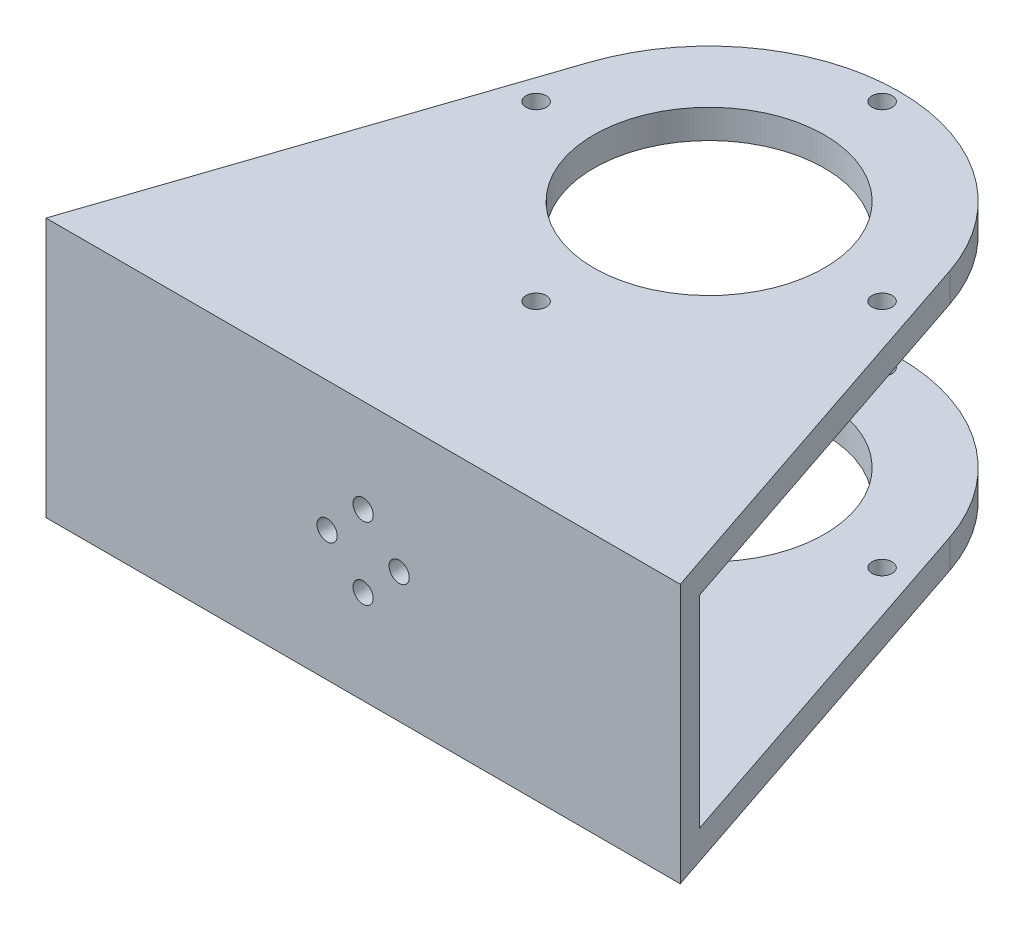
SolidWorks part; units mm, degrees
ref_plane "Front Plane" through (0, 0, 0) normal (0, 0, 1) x (1, 0, 0)
ref_plane "Top Plane" through (0, 0, 0) normal (0, 1, 0) x (1, 0, 0)
ref_plane "Right Plane" through (0, 0, 0) normal (1, 0, 0) x (0, 0, -1)
sketch "Sketch1" plane through (0, 0, 0) normal (0, 1, 0) x (1, 0, 0)
  line L0 (0, 0) -> (0, 56.3962) construction
  line L1 (-39.7228, 13.3621) -> (-69.85, -76.2)
  line L2 (-69.85, -76.2) -> (69.85, -76.2)
  line L3 (39.7228, 13.3621) -> (69.85, -76.2)
  arc A0 (39.7228, 13.3621) -> (-39.7228, 13.3621) centre (0, 0) ccw
  point P9 (0, -76.2)
  dimension "D1" = 139.7
  dimension "D2" = 41.91
  dimension "D3" = 76.2
extrude "Boss-Extrude1" add sketch "Sketch1" along normal blind 57.15 contours L1 L2 L3 A0
sketch "Sketch2" plane through (0, 57.15, 0) normal (0, 1, 0) x (1, 0, 0)
  circle A0 centre (0, 0) radius 25.4
  dimension "D1" = 50.8
extrude "Cut-Extrude1" cut sketch "Sketch2" against normal up to surface (57.15 mm away) up to face at (0, 0, 24.282)
sketch "Sketch3" plane through (0, 57.15, 0) normal (0, 1, 0) x (1, 0, 0)
  circle A0 centre (0, 0) radius 38.1 construction
  circle A1 centre (0, 38.1) radius 2.2225
  dimension "D1" = 76.2
  dimension "D2" = 4.445
extrude "Cut-Extrude2" cut sketch "Sketch3" against normal up to surface (57.15 mm away) contours A1 up to face at (0, 0, 25.4)
pattern_circular "CirPattern1" count 4 over 360 about axis through (0, 0, 0) along (0, 1, 0) of "Cut-Extrude2"
sketch "Sketch4" plane through (0, 0, 0) normal (1, 0, 0) x (0, 0, -1)
  line L0 (-69.85, 6.35) -> (-69.85, 50.8)
  line L1 (-76.2, 57.15) -> (41.91, 57.15) construction
  line L2 (-76.2, 57.15) -> (-76.2, 0) construction
  line L3 (-76.2, 0) -> (41.91, 0) construction
  line L4 (41.91, 57.15) -> (41.91, 0) construction
  line L5 (-17.145, 0) -> (-17.145, 57.15) construction
  line L6 (-69.85, 28.575) -> (41.91, 28.575) construction
  line L7 (-69.85, 50.8) -> (41.91, 50.8)
  line L8 (41.91, 50.8) -> (41.91, 6.35)
  line L9 (-69.85, 6.35) -> (41.91, 6.35)
  point P10 (0, 0)
  point P11 (0, 0)
  point P12 (0, 0)
  point P13 (0, 0)
  point P244 (-17.145, 28.575)
  dimension "D1" = 44.45
  dimension "D2" = 6.35
extrude "Cut-Extrude3" cut sketch "Sketch4" against normal up to surface and the other way up to surface contours L0 L7 L8 L9 up to face at (-54.7864, 28.575, 31.419) other way up to face at (54.7864, 28.575, 31.419)
sketch "Sketch5" plane through (0, 0, 76.2) normal (0, 0, 1) x (1, 0, 0)
  line L1 (-69.85, 57.15) -> (69.85, 57.15) construction
  line L2 (-69.85, 57.15) -> (-69.85, 0) construction
  line L3 (-69.85, 0) -> (69.85, 0) construction
  line L4 (69.85, 57.15) -> (69.85, 0) construction
  line L5 (0, 0) -> (0, 57.15) construction
  line L6 (-69.85, 28.575) -> (69.85, 28.575) construction
  circle A0 centre (0, 28.575) radius 7.9375 construction
  circle A1 centre (0, 36.5125) radius 2.2225
  circle A2 centre (7.9375, 28.575) radius 2.2225
  circle A3 centre (0, 20.6375) radius 2.2225
  circle A4 centre (-7.9375, 28.575) radius 2.2225
  point P68 (0, 28.575)
  dimension "D1" = 15.875
  dimension "D2" = 4.445
  dimension "D3" = 4.445
  dimension "D4" = 4.445
  dimension "D5" = 4.445
extrude "Cut-Extrude4" cut sketch "Sketch5" against normal up to surface (6.35 mm away) contours A1 | A4 | A3 | A2 up to face at (0, 28.575, 69.85)
